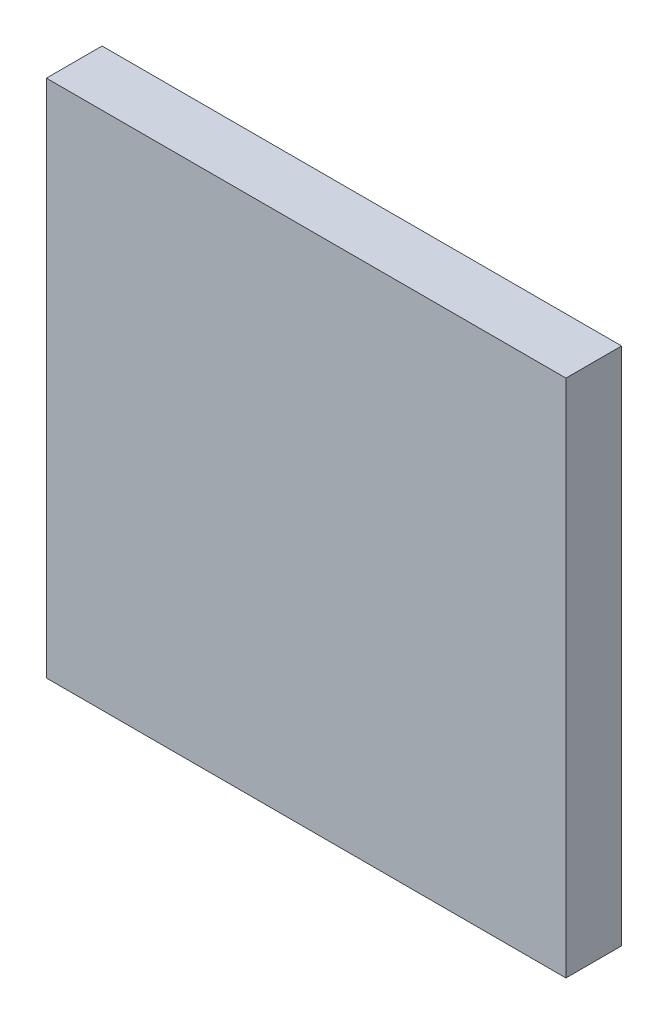
SolidWorks part; units mm, degrees
ref_plane "Front Plane" through (0, 0, 0) normal (0, 0, 1) x (1, 0, 0)
ref_plane "Top Plane" through (0, 0, 0) normal (0, 1, 0) x (1, 0, 0)
ref_plane "Right Plane" through (0, 0, 0) normal (1, 0, 0) x (0, 0, -1)
sketch "Sketch2" plane through (0, 0, 0) normal (0, 0, 1) x (1, 0, 0)
  line L1 (-14, 14) -> (14, 14)
  line L2 (-14, 14) -> (-14, -14)
  line L3 (-14, -14) -> (14, -14)
  line L4 (14, 14) -> (14, -14)
  line L5 (-14, 14) -> (14, -14) construction
  line L6 (-14, -14) -> (14, 14) construction
  point P0 (0, 0)
  dimension "D1" = 28
  dimension "D2" = 28
extrude "Boss-Extrude1" add sketch "Sketch2" along normal blind 3
